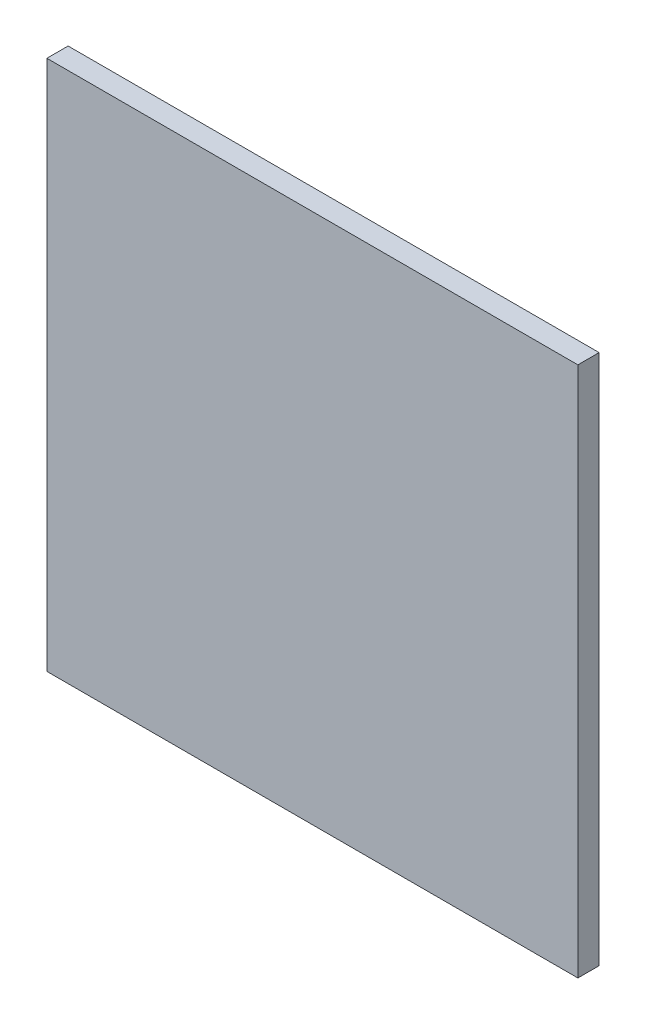
SolidWorks part; units mm, degrees
ref_plane "Front Plane" through (0, 0, 0) normal (0, 0, 1) x (1, 0, 0)
ref_plane "Top Plane" through (0, 0, 0) normal (0, 1, 0) x (1, 0, 0)
ref_plane "Right Plane" through (0, 0, 0) normal (1, 0, 0) x (0, 0, -1)
sketch "Sketch1" plane through (0, 0, 0) normal (0, 0, 1) x (1, 0, 0)
  line L1 (-23.3223, 15.2333) -> (6.6777, 15.2333)
  line L2 (-23.3223, 15.2333) -> (-23.3223, -14.7667)
  line L3 (-23.3223, -14.7667) -> (6.6777, -14.7667)
  line L4 (6.6777, 15.2333) -> (6.6777, -14.7667)
  dimension "D1" = 30
  dimension "D2" = 30
extrude "Boss-Extrude1" add sketch "Sketch1" along normal blind 1.2
